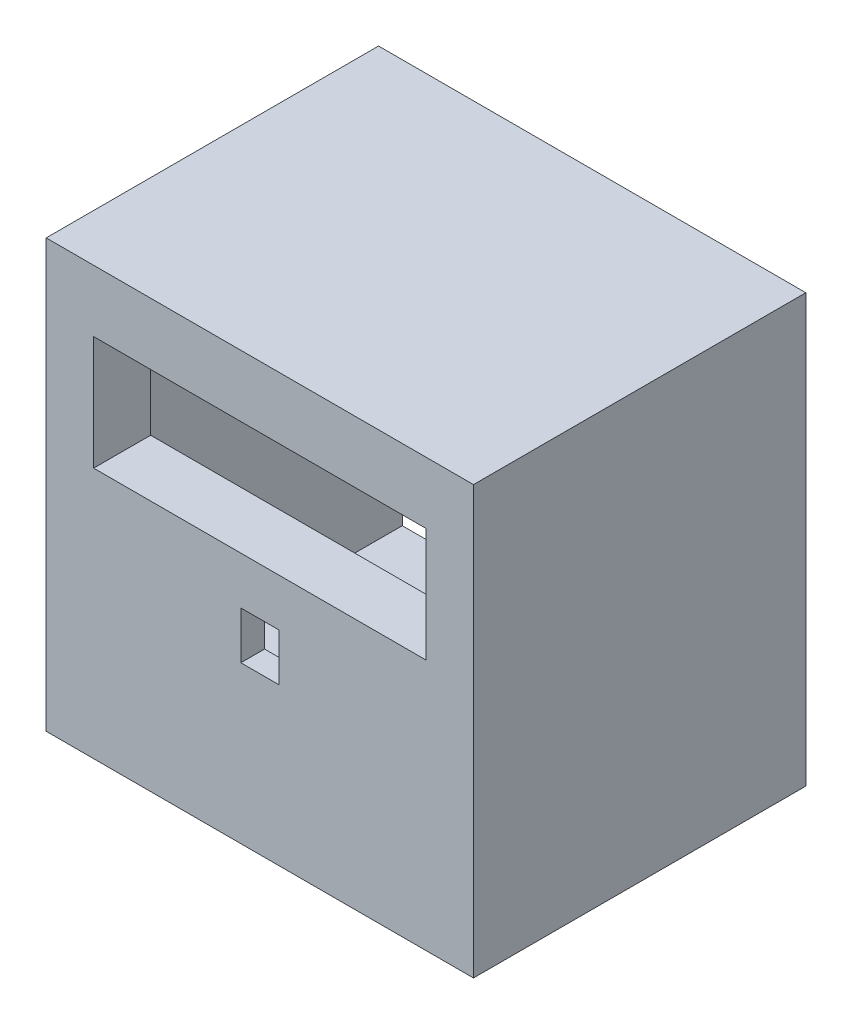
SolidWorks part; units mm, degrees
ref_plane "Front Plane" through (0, 0, 0) normal (0, 0, 1) x (1, 0, 0)
ref_plane "Top Plane" through (0, 0, 0) normal (0, 1, 0) x (1, 0, 0)
ref_plane "Right Plane" through (0, 0, 0) normal (1, 0, 0) x (0, 0, -1)
sketch "Sketch1" plane through (0, 0, 0) normal (0, 0, 1) x (1, 0, 0)
  line L1 (-45, -45) -> (45, -45)
  line L2 (-45, -45) -> (-45, 45)
  line L3 (-45, 45) -> (45, 45)
  line L4 (45, -45) -> (45, 45)
  line L5 (-45, -45) -> (45, 45) construction
  line L6 (-45, 45) -> (45, -45) construction
  point P0 (0, 0)
  dimension "D1" = 90
  dimension "D2" = 90
extrude "Boss-Extrude1" add sketch "Sketch1" along normal blind 70
shell "Shell2" thickness 5
sketch "Sketch2" plane through (0, 0, 70) normal (0, 0, 1) x (1, 0, 0)
  line L0 (0, 45) -> (0, -45) construction
  line L1 (45, 45) -> (-45, 45) construction
  line L2 (-45, -45) -> (45, -45) construction
  line L4 (-35, 8) -> (35, 8)
  line L5 (-35, 8) -> (-35, 32)
  line L6 (-35, 32) -> (35, 32)
  line L7 (35, 8) -> (35, 32)
  line L8 (-35, 8) -> (35, 32) construction
  line L9 (-35, 32) -> (35, 8) construction
  point P6 (0, 20)
  point P12 (0, 20)
  dimension "D1" = 70
  dimension "D2" = 24
  dimension "D3" = 25
extrude "Cut-Extrude1" cut sketch "Sketch2" against normal up to next contours L4 L7 L6 L5
sketch "Sketch4" plane through (0, 0, 65) normal (0, 0, -1) x (-1, 0, 0)
  line L0 (-40, 32) -> (35, 32)
  line L1 (-40, 2) -> (40, 2)
  line L2 (-40, 2) -> (-40, 38)
  line L3 (-40, 38) -> (40, 38)
  line L4 (40, 2) -> (40, 38)
  line L5 (-40, 2) -> (40, 38) construction
  line L6 (-40, 38) -> (40, 2) construction
  line L7 (35, 32) -> (35, 8)
  line L8 (35, 8) -> (-40, 8)
  point P0 (0, 20)
  line M3 (35, 8) -> (-35, 8)
  line M5 (-35, 32) -> (35, 32)
  line M6 (35, 32) -> (35, 8)
  line M7 (-40, 40) -> (-40, -40)
  line M9 (40, -40) -> (40, 40)
  dimension "D1" = 80
  dimension "D2" = 36
extrude "Boss-Extrude2" add sketch "Sketch4" along normal blind 7 contours L8 L2 L1 L3 L0 M3 M9 M7 M5 M6
sketch "Sketch5" plane through (0, 0, 70) normal (0, 0, 1) x (1, 0, 0)
  line L0 (0, 45) -> (0, -45) construction
  line L1 (-4, -12) -> (4, -12)
  line L2 (-4, -12) -> (-4, -2)
  line L3 (-4, -2) -> (4, -2)
  line L4 (4, -12) -> (4, -2)
  line L5 (-4, -12) -> (4, -2) construction
  line L6 (-4, -2) -> (4, -12) construction
  line L7 (-35, 8) -> (35, 8) construction
  point P0 (0, -7)
  point P5 (9.5862, -7)
  point P6 (0, 0)
  point P7 (0, -6.0693)
  point P10 (0, 0)
  dimension "D1" = 8
  dimension "D2" = 10
  dimension "D3" = 15
extrude "Cut-Extrude2" cut sketch "Sketch5" against normal blind 10
